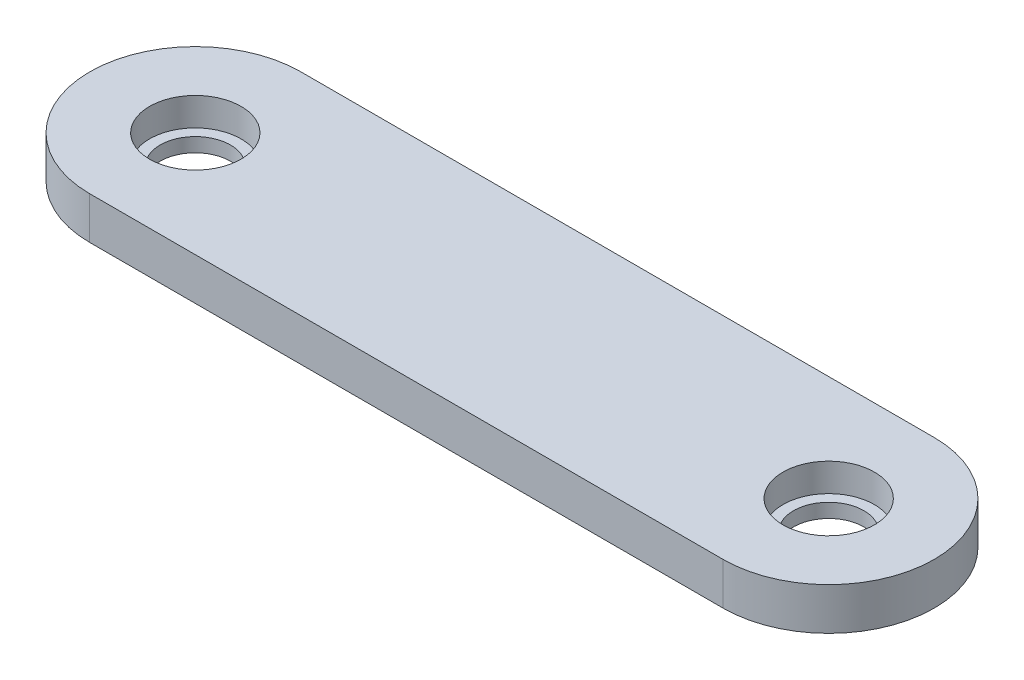
SolidWorks part; units mm, degrees
ref_plane "Front Plane" through (0, 0, 0) normal (0, 0, 1) x (1, 0, 0)
ref_plane "Top Plane" through (0, 0, 0) normal (0, 1, 0) x (1, 0, 0)
ref_plane "Right Plane" through (0, 0, 0) normal (1, 0, 0) x (0, 0, -1)
sketch "Sketch2" plane through (0, 0, 0) normal (0, 1, 0) x (1, 0, 0)
  line L1 (-45, 15) -> (45, 15)
  line L3 (-45, -15) -> (45, -15)
  arc A0 (-45, 15) -> (-45, -15) centre (-45, 0) ccw
  arc A1 (45, -15) -> (45, 15) centre (45, 0) ccw
  circle A2 centre (-45, 0) radius 5
  circle A3 centre (45, 0) radius 5
  point P0 (0, 0)
extrude "Boss-Extrude1" add sketch "Sketch2" along normal blind 6
sketch "Sketch3" plane through (0, 6, 0) normal (0, 1, 0) x (1, 0, 0)
  circle A0 centre (-45, 0) radius 6.5
  circle A1 centre (45, 0) radius 6.5
extrude "Cut-Extrude1" cut sketch "Sketch3" against normal blind 4
